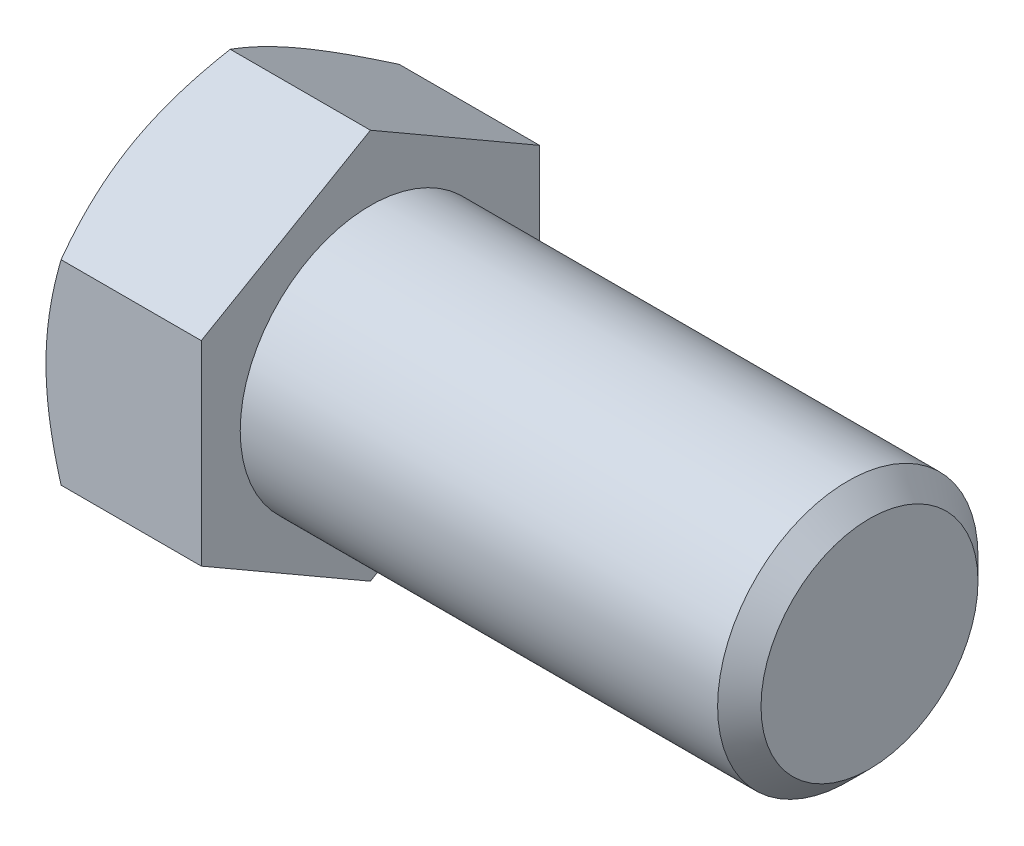
SolidWorks part; units mm, degrees
ref_plane "Спереди" through (0, 0, 0) normal (0, 0, 1) x (1, 0, 0)
ref_plane "Сверху" through (0, 0, 0) normal (0, 1, 0) x (1, 0, 0)
ref_plane "Справа" through (0, 0, 0) normal (1, 0, 0) x (0, 0, -1)
sketch "Эскиз1" plane through (0, 0, 0) normal (0, 0, 1) x (1, 0, 0)
  line L0 (0, 0) -> (23, 0)
  line L1 (23, 0) -> (23, 6)
  line L5 (0, 6) -> (0, 9)
  line L6 (0, 9) -> (-6.4608, 9)
  line L7 (-6.4608, 9) -> (-7.5, 7.2)
  line L8 (-7.5, 7.2) -> (-7.5, 0)
  line L9 (-7.5, 0) -> (0, 0)
  line L10 (0, 6) -> (23, 6)
  dimension "D1" = 7.5
  dimension "D2" = 23
  dimension "D3" = 6
  dimension "D4" = 30
  dimension "D5" = 7.2
  dimension "D6" = 9
revolve "Повернуть1" add sketch "Эскиз1" angle 360 about L0
sketch "Эскиз2" plane through (0, 0, 0) normal (1, 0, 0) x (0, 0, -1)
  line L7 (7.7942, 4.5) -> (0, 9)
  line L8 (0, 9) -> (-7.7942, 4.5)
  line L9 (-7.7942, 4.5) -> (-7.7942, -4.5)
  line L10 (-7.7942, -4.5) -> (0, -9)
  line L11 (0, -9) -> (7.7942, -4.5)
  line L12 (7.7942, -4.5) -> (7.7942, 4.5)
  circle A1 centre (0, 0) radius 7.7942 construction
  circle A2 centre (0, 0) radius 9 construction
  circle A3 centre (0, 0) radius 9
ref_plane "Плоскость1" through (-2, 0, 0) normal (1, 0, 0) x (0, 0, -1)
sketch "Эскиз3" plane through (-2, 0, 0) normal (1, 0, 0) x (0, 0, -1)
  circle A0 centre (0, 0) radius 10
curve "Спираль1"
sketch "Эскиз4" plane through (23, 0, 0) normal (1, 0, 0) x (0, 0, -1)
  circle A0 centre (0, 0) radius 10
curve "Спираль2" pitch 1.25 height 25 turns 20
extrude "Вырез-Вытянуть1" cut sketch "Эскиз2" against normal blind 10 flip side to cut contours L8 L9 L10 L11 L12 L7
chamfer "Фаска1" distance 1 angle 45 1 edges at (23, 0, 6)
equation "\"p\"= 1.25"
equation "\"D1@Эскиз5\"=\"p\"/2"
equation "\"D3@Эскиз5\"=\"p\"/4"
equation "\"D4@Эскиз5\"=\"p\"/8"
